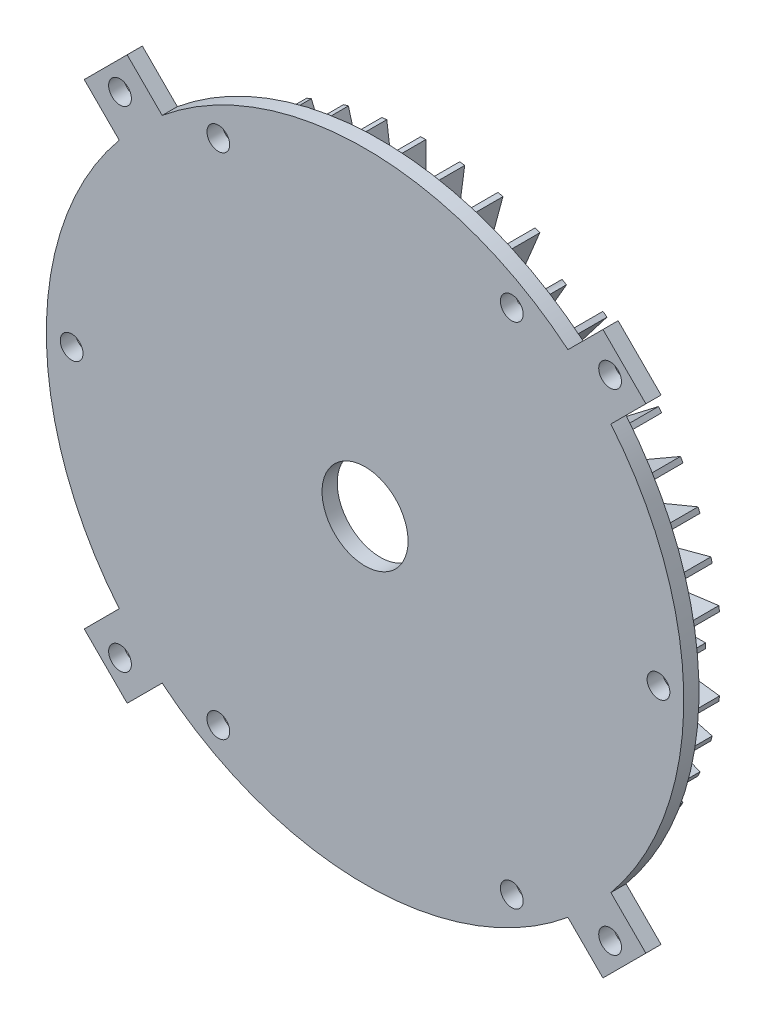
SolidWorks part; units mm, degrees
ref_plane "Спереди" through (0, 0, 0) normal (0, 0, 1) x (1, 0, 0)
ref_plane "Сверху" through (0, 0, 0) normal (0, 1, 0) x (1, 0, 0)
ref_plane "Справа" through (0, 0, 0) normal (1, 0, 0) x (0, 0, -1)
sketch "Эскиз1" plane through (0, 0, 0) normal (0, 0, 1) x (1, 0, 0)
  circle A0 centre (0, 0) radius 63
  circle A1 centre (0, 0) radius 8.5
extrude "Heat_spreader" add sketch "Эскиз1" along normal blind 3 from offset 35
sketch "Эскиз2" plane through (0, 0, 0) normal (0, 0, 1) x (1, 0, 0)
  line L0 (44.5477, 36.0624) -> (55.5079, 47.0226)
  line L1 (55.5079, 47.0226) -> (47.0226, 55.5079)
  line L2 (47.0226, 55.5079) -> (36.0624, 44.5477)
  line L3 (36.0624, 44.5477) -> (44.5477, 36.0624)
  line L4 (-36.0624, 44.5477) -> (-47.0226, 55.5079)
  line L5 (-47.0226, 55.5079) -> (-55.5079, 47.0226)
  line L6 (-55.5079, 47.0226) -> (-44.5477, 36.0624)
  line L7 (-44.5477, 36.0624) -> (-36.0624, 44.5477)
  line L8 (-44.5477, -36.0624) -> (-55.5079, -47.0226)
  line L9 (-55.5079, -47.0226) -> (-47.0226, -55.5079)
  line L10 (-47.0226, -55.5079) -> (-36.0624, -44.5477)
  line L11 (-36.0624, -44.5477) -> (-44.5477, -36.0624)
  line L12 (36.0624, -44.5477) -> (47.0226, -55.5079)
  line L13 (47.0226, -55.5079) -> (55.5079, -47.0226)
  line L14 (55.5079, -47.0226) -> (44.5477, -36.0624)
  line L15 (44.5477, -36.0624) -> (36.0624, -44.5477)
extrude "Tie_rod_ears" add sketch "Эскиз2" along normal blind 3 from offset 35
sketch "Эскиз3" plane through (0, 0, 0) normal (0, 0, 1) x (1, 0, 0)
  line L0 (26, -0.5) -> (59, -0.5)
  line L1 (59, -0.5) -> (59, 0.5)
  line L2 (59, 0.5) -> (26, 0.5)
  line L3 (26, 0.5) -> (26, -0.5)
  line L4 (25.8428, 2.898) -> (58.5605, 7.2053)
  line L5 (58.5605, 7.2053) -> (58.43, 8.1968)
  line L6 (58.43, 8.1968) -> (25.7123, 3.8894)
  line L7 (25.7123, 3.8894) -> (25.8428, 2.898)
  line L8 (25.2435, 6.2463) -> (57.119, 14.7874)
  line L9 (57.119, 14.7874) -> (56.8602, 15.7533)
  line L10 (56.8602, 15.7533) -> (24.9847, 7.2123)
  line L11 (24.9847, 7.2123) -> (25.2435, 6.2463)
  line L12 (24.2122, 9.4878) -> (54.7002, 22.1164)
  line L13 (54.7002, 22.1164) -> (54.3176, 23.0403)
  line L14 (54.3176, 23.0403) -> (23.8295, 10.4117)
  line L15 (23.8295, 10.4117) -> (24.2122, 9.4878)
  line L16 (22.7667, 12.567) -> (51.3455, 29.067)
  line L17 (51.3455, 29.067) -> (50.8455, 29.933)
  line L18 (50.8455, 29.933) -> (22.2667, 13.433)
  line L19 (22.2667, 13.433) -> (22.7667, 12.567)
  line L20 (20.9316, 15.4311) -> (47.1122, 35.5202)
  line L21 (47.1122, 35.5202) -> (46.5035, 36.3136)
  line L22 (46.5035, 36.3136) -> (20.3228, 16.2245)
  line L23 (20.3228, 16.2245) -> (20.9316, 15.4311)
  line L24 (18.7383, 18.0312) -> (42.0729, 41.3657)
  line L25 (42.0729, 41.3657) -> (41.3657, 42.0729)
  line L26 (41.3657, 42.0729) -> (18.0312, 18.7383)
  line L27 (18.0312, 18.7383) -> (18.7383, 18.0312)
  line L28 (16.2245, 20.3228) -> (36.3136, 46.5035)
  line L29 (36.3136, 46.5035) -> (35.5202, 47.1122)
  line L30 (35.5202, 47.1122) -> (15.4311, 20.9316)
  line L31 (15.4311, 20.9316) -> (16.2245, 20.3228)
  line L32 (13.433, 22.2667) -> (29.933, 50.8455)
  line L33 (29.933, 50.8455) -> (29.067, 51.3455)
  line L34 (29.067, 51.3455) -> (12.567, 22.7667)
  line L35 (12.567, 22.7667) -> (13.433, 22.2667)
  line L36 (10.4117, 23.8295) -> (23.0403, 54.3176)
  line L37 (23.0403, 54.3176) -> (22.1164, 54.7002)
  line L38 (22.1164, 54.7002) -> (9.4878, 24.2122)
  line L39 (9.4878, 24.2122) -> (10.4117, 23.8295)
  line L40 (7.2123, 24.9847) -> (15.7533, 56.8602)
  line L41 (15.7533, 56.8602) -> (14.7874, 57.119)
  line L42 (14.7874, 57.119) -> (6.2463, 25.2435)
  line L43 (6.2463, 25.2435) -> (7.2123, 24.9847)
  line L44 (3.8894, 25.7123) -> (8.1968, 58.43)
  line L45 (8.1968, 58.43) -> (7.2053, 58.5605)
  line L46 (7.2053, 58.5605) -> (2.898, 25.8428)
  line L47 (2.898, 25.8428) -> (3.8894, 25.7123)
  line L48 (0.5, 26) -> (0.5, 59)
  line L49 (0.5, 59) -> (-0.5, 59)
  line L50 (-0.5, 59) -> (-0.5, 26)
  line L51 (-0.5, 26) -> (0.5, 26)
  line L52 (-2.898, 25.8428) -> (-7.2053, 58.5605)
  line L53 (-7.2053, 58.5605) -> (-8.1968, 58.43)
  line L54 (-8.1968, 58.43) -> (-3.8894, 25.7123)
  line L55 (-3.8894, 25.7123) -> (-2.898, 25.8428)
  line L56 (-6.2463, 25.2435) -> (-14.7874, 57.119)
  line L57 (-14.7874, 57.119) -> (-15.7533, 56.8602)
  line L58 (-15.7533, 56.8602) -> (-7.2123, 24.9847)
  line L59 (-7.2123, 24.9847) -> (-6.2463, 25.2435)
  line L60 (-9.4878, 24.2122) -> (-22.1164, 54.7002)
  line L61 (-22.1164, 54.7002) -> (-23.0403, 54.3176)
  line L62 (-23.0403, 54.3176) -> (-10.4117, 23.8295)
  line L63 (-10.4117, 23.8295) -> (-9.4878, 24.2122)
  line L64 (-12.567, 22.7667) -> (-29.067, 51.3455)
  line L65 (-29.067, 51.3455) -> (-29.933, 50.8455)
  line L66 (-29.933, 50.8455) -> (-13.433, 22.2667)
  line L67 (-13.433, 22.2667) -> (-12.567, 22.7667)
  line L68 (-15.4311, 20.9316) -> (-35.5202, 47.1122)
  line L69 (-35.5202, 47.1122) -> (-36.3136, 46.5035)
  line L70 (-36.3136, 46.5035) -> (-16.2245, 20.3228)
  line L71 (-16.2245, 20.3228) -> (-15.4311, 20.9316)
  line L72 (-18.0312, 18.7383) -> (-41.3657, 42.0729)
  line L73 (-41.3657, 42.0729) -> (-42.0729, 41.3657)
  line L74 (-42.0729, 41.3657) -> (-18.7383, 18.0312)
  line L75 (-18.7383, 18.0312) -> (-18.0312, 18.7383)
  line L76 (-20.3228, 16.2245) -> (-46.5035, 36.3136)
  line L77 (-46.5035, 36.3136) -> (-47.1122, 35.5202)
  line L78 (-47.1122, 35.5202) -> (-20.9316, 15.4311)
  line L79 (-20.9316, 15.4311) -> (-20.3228, 16.2245)
  line L80 (-22.2667, 13.433) -> (-50.8455, 29.933)
  line L81 (-50.8455, 29.933) -> (-51.3455, 29.067)
  line L82 (-51.3455, 29.067) -> (-22.7667, 12.567)
  line L83 (-22.7667, 12.567) -> (-22.2667, 13.433)
  line L84 (-23.8295, 10.4117) -> (-54.3176, 23.0403)
  line L85 (-54.3176, 23.0403) -> (-54.7002, 22.1164)
  line L86 (-54.7002, 22.1164) -> (-24.2122, 9.4878)
  line L87 (-24.2122, 9.4878) -> (-23.8295, 10.4117)
  line L88 (-24.9847, 7.2123) -> (-56.8602, 15.7533)
  line L89 (-56.8602, 15.7533) -> (-57.119, 14.7874)
  line L90 (-57.119, 14.7874) -> (-25.2435, 6.2463)
  line L91 (-25.2435, 6.2463) -> (-24.9847, 7.2123)
  line L92 (-25.7123, 3.8894) -> (-58.43, 8.1968)
  line L93 (-58.43, 8.1968) -> (-58.5605, 7.2053)
  line L94 (-58.5605, 7.2053) -> (-25.8428, 2.898)
  line L95 (-25.8428, 2.898) -> (-25.7123, 3.8894)
  line L96 (-26, 0.5) -> (-59, 0.5)
  line L97 (-59, 0.5) -> (-59, -0.5)
  line L98 (-59, -0.5) -> (-26, -0.5)
  line L99 (-26, -0.5) -> (-26, 0.5)
  line L100 (-25.8428, -2.898) -> (-58.5605, -7.2053)
  line L101 (-58.5605, -7.2053) -> (-58.43, -8.1968)
  line L102 (-58.43, -8.1968) -> (-25.7123, -3.8894)
  line L103 (-25.7123, -3.8894) -> (-25.8428, -2.898)
  line L104 (-25.2435, -6.2463) -> (-57.119, -14.7874)
  line L105 (-57.119, -14.7874) -> (-56.8602, -15.7533)
  line L106 (-56.8602, -15.7533) -> (-24.9847, -7.2123)
  line L107 (-24.9847, -7.2123) -> (-25.2435, -6.2463)
  line L108 (-24.2122, -9.4878) -> (-54.7002, -22.1164)
  line L109 (-54.7002, -22.1164) -> (-54.3176, -23.0403)
  line L110 (-54.3176, -23.0403) -> (-23.8295, -10.4117)
  line L111 (-23.8295, -10.4117) -> (-24.2122, -9.4878)
  line L112 (-22.7667, -12.567) -> (-51.3455, -29.067)
  line L113 (-51.3455, -29.067) -> (-50.8455, -29.933)
  line L114 (-50.8455, -29.933) -> (-22.2667, -13.433)
  line L115 (-22.2667, -13.433) -> (-22.7667, -12.567)
  line L116 (-20.9316, -15.4311) -> (-47.1122, -35.5202)
  line L117 (-47.1122, -35.5202) -> (-46.5035, -36.3136)
  line L118 (-46.5035, -36.3136) -> (-20.3228, -16.2245)
  line L119 (-20.3228, -16.2245) -> (-20.9316, -15.4311)
  line L120 (-18.7383, -18.0312) -> (-42.0729, -41.3657)
  line L121 (-42.0729, -41.3657) -> (-41.3657, -42.0729)
  line L122 (-41.3657, -42.0729) -> (-18.0312, -18.7383)
  line L123 (-18.0312, -18.7383) -> (-18.7383, -18.0312)
  line L124 (-16.2245, -20.3228) -> (-36.3136, -46.5035)
  line L125 (-36.3136, -46.5035) -> (-35.5202, -47.1122)
  line L126 (-35.5202, -47.1122) -> (-15.4311, -20.9316)
  line L127 (-15.4311, -20.9316) -> (-16.2245, -20.3228)
  line L128 (-13.433, -22.2667) -> (-29.933, -50.8455)
  line L129 (-29.933, -50.8455) -> (-29.067, -51.3455)
  line L130 (-29.067, -51.3455) -> (-12.567, -22.7667)
  line L131 (-12.567, -22.7667) -> (-13.433, -22.2667)
  line L132 (-10.4117, -23.8295) -> (-23.0403, -54.3176)
  line L133 (-23.0403, -54.3176) -> (-22.1164, -54.7002)
  line L134 (-22.1164, -54.7002) -> (-9.4878, -24.2122)
  line L135 (-9.4878, -24.2122) -> (-10.4117, -23.8295)
  line L136 (-7.2123, -24.9847) -> (-15.7533, -56.8602)
  line L137 (-15.7533, -56.8602) -> (-14.7874, -57.119)
  line L138 (-14.7874, -57.119) -> (-6.2463, -25.2435)
  line L139 (-6.2463, -25.2435) -> (-7.2123, -24.9847)
  line L140 (-3.8894, -25.7123) -> (-8.1968, -58.43)
  line L141 (-8.1968, -58.43) -> (-7.2053, -58.5605)
  line L142 (-7.2053, -58.5605) -> (-2.898, -25.8428)
  line L143 (-2.898, -25.8428) -> (-3.8894, -25.7123)
  line L144 (-0.5, -26) -> (-0.5, -59)
  line L145 (-0.5, -59) -> (0.5, -59)
  line L146 (0.5, -59) -> (0.5, -26)
  line L147 (0.5, -26) -> (-0.5, -26)
  line L148 (2.898, -25.8428) -> (7.2053, -58.5605)
  line L149 (7.2053, -58.5605) -> (8.1968, -58.43)
  line L150 (8.1968, -58.43) -> (3.8894, -25.7123)
  line L151 (3.8894, -25.7123) -> (2.898, -25.8428)
  line L152 (6.2463, -25.2435) -> (14.7874, -57.119)
  line L153 (14.7874, -57.119) -> (15.7533, -56.8602)
  line L154 (15.7533, -56.8602) -> (7.2123, -24.9847)
  line L155 (7.2123, -24.9847) -> (6.2463, -25.2435)
  line L156 (9.4878, -24.2122) -> (22.1164, -54.7002)
  line L157 (22.1164, -54.7002) -> (23.0403, -54.3176)
  line L158 (23.0403, -54.3176) -> (10.4117, -23.8295)
  line L159 (10.4117, -23.8295) -> (9.4878, -24.2122)
  line L160 (12.567, -22.7667) -> (29.067, -51.3455)
  line L161 (29.067, -51.3455) -> (29.933, -50.8455)
  line L162 (29.933, -50.8455) -> (13.433, -22.2667)
  line L163 (13.433, -22.2667) -> (12.567, -22.7667)
  line L164 (15.4311, -20.9316) -> (35.5202, -47.1122)
  line L165 (35.5202, -47.1122) -> (36.3136, -46.5035)
  line L166 (36.3136, -46.5035) -> (16.2245, -20.3228)
  line L167 (16.2245, -20.3228) -> (15.4311, -20.9316)
  line L168 (18.0312, -18.7383) -> (41.3657, -42.0729)
  line L169 (41.3657, -42.0729) -> (42.0729, -41.3657)
  line L170 (42.0729, -41.3657) -> (18.7383, -18.0312)
  line L171 (18.7383, -18.0312) -> (18.0312, -18.7383)
  line L172 (20.3228, -16.2245) -> (46.5035, -36.3136)
  line L173 (46.5035, -36.3136) -> (47.1122, -35.5202)
  line L174 (47.1122, -35.5202) -> (20.9316, -15.4311)
  line L175 (20.9316, -15.4311) -> (20.3228, -16.2245)
  line L176 (22.2667, -13.433) -> (50.8455, -29.933)
  line L177 (50.8455, -29.933) -> (51.3455, -29.067)
  line L178 (51.3455, -29.067) -> (22.7667, -12.567)
  line L179 (22.7667, -12.567) -> (22.2667, -13.433)
  line L180 (23.8295, -10.4117) -> (54.3176, -23.0403)
  line L181 (54.3176, -23.0403) -> (54.7002, -22.1164)
  line L182 (54.7002, -22.1164) -> (24.2122, -9.4878)
  line L183 (24.2122, -9.4878) -> (23.8295, -10.4117)
  line L184 (24.9847, -7.2123) -> (56.8602, -15.7533)
  line L185 (56.8602, -15.7533) -> (57.119, -14.7874)
  line L186 (57.119, -14.7874) -> (25.2435, -6.2463)
  line L187 (25.2435, -6.2463) -> (24.9847, -7.2123)
  line L188 (25.7123, -3.8894) -> (58.43, -8.1968)
  line L189 (58.43, -8.1968) -> (58.5605, -7.2053)
  line L190 (58.5605, -7.2053) -> (25.8428, -2.898)
  line L191 (25.8428, -2.898) -> (25.7123, -3.8894)
extrude "Cooling_fins" add sketch "Эскиз3" along normal blind 8.5 from offset 43.5
sketch "Эскиз4" plane through (0, 0, 0) normal (0, 0, 1) x (1, 0, 0)
  circle A0 centre (48.4368, 48.4368) radius 2.25
  circle A1 centre (-48.4368, 48.4368) radius 2.25
  circle A2 centre (-48.4368, -48.4368) radius 2.25
  circle A3 centre (48.4368, -48.4368) radius 2.25
  circle A4 centre (58, 0) radius 2.25
  circle A5 centre (29, 50.2295) radius 2.25
  circle A6 centre (-29, 50.2295) radius 2.25
  circle A7 centre (-58, 0) radius 2.25
  circle A8 centre (-29, -50.2295) radius 2.25
  circle A9 centre (29, -50.2295) radius 2.25
extrude "Through_holes" cut sketch "Эскиз4" against normal mid plane 200
